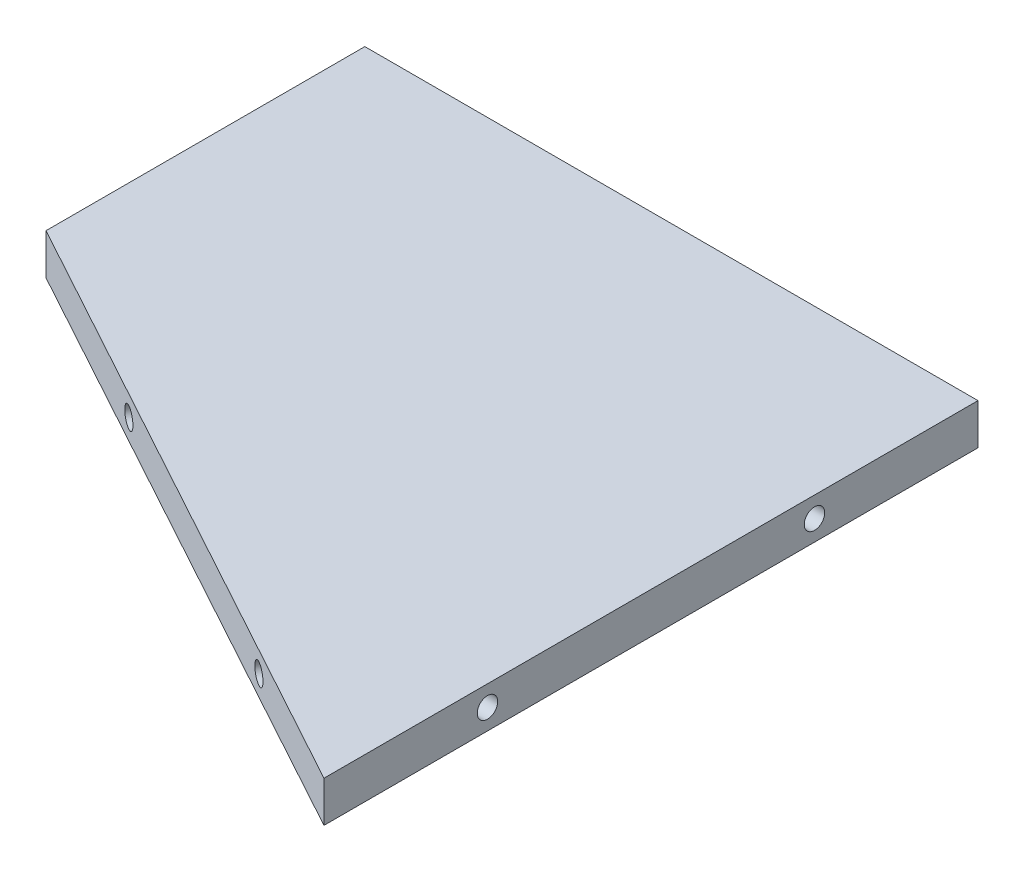
SolidWorks part; units mm, degrees
material "Acrylic"
ref_plane "Front" through (0, 0, 0) normal (0, 0, 1) x (1, 0, 0)
ref_plane "Top" through (0, 0, 0) normal (0, 1, 0) x (1, 0, 0)
ref_plane "Right" through (0, 0, 0) normal (1, 0, 0) x (0, 0, -1)
sketch "Sketch1" plane through (0, 0, 0) normal (0, 1, 0) x (1, 0, 0)
  line L0 (0, -39) -> (75, -80)
  line L1 (0, 0) -> (75, 0)
  line L2 (0, 0) -> (0, -39)
  line L4 (75, 0) -> (75, -80)
  dimension "D1" = 39
  dimension "D2" = 80
  dimension "D3" = 75
extrude "Boss-Extrude1" add sketch "Sketch1" against normal blind 5
hole_wizard "M3x0.5 Tapped Hole1" positions "Sketch2" profile "Sketch3" tap size "M3x0.5" standard "JIS"
sketch "Sketch2" plane through (0, 0, 0) normal (0, 0, -1) x (-1, 0, 0)
  line L0 (0, -5) -> (0, 0) construction
  line L1 (-75, -5) -> (0, -5) construction
  point P0 (-15, -2.5)
  point P2 (-60, -2.5)
  dimension "D1" = 15
  dimension "D2" = 60
  dimension "D3" = 2.5
sketch "Sketch3" plane through (15, -2.5, 0) normal (1, 0, 0) x (0, 1, 0)
  line L0 (0, 0) -> (0, 8.2511)
  line L1 (0, 8.2511) -> (1.25, 7.5)
  line L2 (1.25, 7.5) -> (1.25, 0)
  line L5 (1.25, 0) -> (0, 0)
  line L10 (0, 8.2511) -> (-1.25, 7.5) construction
  line L11 (0, -6.35) -> (0, 107.95) construction
  dimension "Tap Drill Dia." = 2.5
  dimension "Tap Drill Depth" = 7.5
  dimension "Drill Angle" = 118
cosmetic thread "Hole Thread1"
cosmetic thread "Hole Thread2"
hole_wizard "M3x0.5 Tapped Hole2" positions "Sketch4" profile "Sketch5" tap size "M3x0.5" standard "JIS"
sketch "Sketch4" plane through (0, 0, 0) normal (-1, 0, 0) x (0, 0, 1)
  line L0 (0, -5) -> (0, 0) construction
  line L1 (0, -5) -> (39, -5) construction
  point P0 (10, -2.5)
  point P2 (25, -2.5)
  dimension "D1" = 10
  dimension "D2" = 25
  dimension "D3" = 2.5
sketch "Sketch5" plane through (0, -2.5, 10) normal (0, 1, 0) x (0, 0, 1)
  line L0 (0, 0) -> (0, 8.2511)
  line L1 (0, 8.2511) -> (1.25, 7.5)
  line L2 (1.25, 7.5) -> (1.25, 0)
  line L5 (1.25, 0) -> (0, 0)
  line L10 (0, 8.2511) -> (-1.25, 7.5) construction
  line L11 (0, -6.35) -> (0, 107.95) construction
  dimension "Tap Drill Dia." = 2.5
  dimension "Tap Drill Depth" = 7.5
  dimension "Drill Angle" = 118
cosmetic thread "Hole Thread3"
cosmetic thread "Hole Thread4"
hole_wizard "M3x0.5 Tapped Hole3" positions "Sketch6" profile "Sketch7" tap size "M3x0.5" standard "JIS"
sketch "Sketch6" plane through (75, 0, 0) normal (1, 0, 0) x (0, 0, -1)
  line L0 (-80, -5) -> (-80, 0) construction
  line L1 (-80, -5) -> (0, -5) construction
  point P0 (-20, -2.5)
  point P2 (-60, -2.5)
  dimension "D1" = 60
  dimension "D2" = 20
  dimension "D3" = 2.5
sketch "Sketch7" plane through (75, -2.5, 20) normal (0, 1, 0) x (0, 0, -1)
  line L0 (0, 0) -> (0, 8.2511)
  line L1 (0, 8.2511) -> (1.25, 7.5)
  line L2 (1.25, 7.5) -> (1.25, 0)
  line L5 (1.25, 0) -> (0, 0)
  line L10 (0, 8.2511) -> (-1.25, 7.5) construction
  line L11 (0, -6.35) -> (0, 107.95) construction
  dimension "Tap Drill Dia." = 2.5
  dimension "Tap Drill Depth" = 7.5
  dimension "Drill Angle" = 118
cosmetic thread "Hole Thread5"
cosmetic thread "Hole Thread6"
hole_wizard "M3x0.5 Tapped Hole4" positions "Sketch8" profile "Sketch9" tap size "M3x0.5" standard "JIS"
sketch "Sketch8" plane through (-16.4146, 0, 30.0267) normal (-0.4797, 0, 0.8774) x (0.8774, 0, 0.4797)
  line L0 (18.7072, -5) -> (104.1823, -5) construction
  line L1 (104.1823, -5) -> (104.1823, 0) construction
  point P0 (44.1823, -2.5)
  point P2 (84.1823, -2.5)
  dimension "D1" = 2.5
  dimension "D2" = 20
  dimension "D3" = 60
sketch "Sketch9" plane through (22.3531, -2.5, 51.2197) normal (0, 1, 0) x (0.8774, 0, 0.4797)
  line L0 (0, 0) -> (0, 8.2511)
  line L1 (0, 8.2511) -> (1.25, 7.5)
  line L2 (1.25, 7.5) -> (1.25, 0)
  line L5 (1.25, 0) -> (0, 0)
  line L10 (0, 8.2511) -> (-1.25, 7.5) construction
  line L11 (0, -6.35) -> (0, 107.95) construction
  dimension "Tap Drill Dia." = 2.5
  dimension "Tap Drill Depth" = 7.5
  dimension "Drill Angle" = 118
cosmetic thread "Hole Thread7"
cosmetic thread "Hole Thread8"
